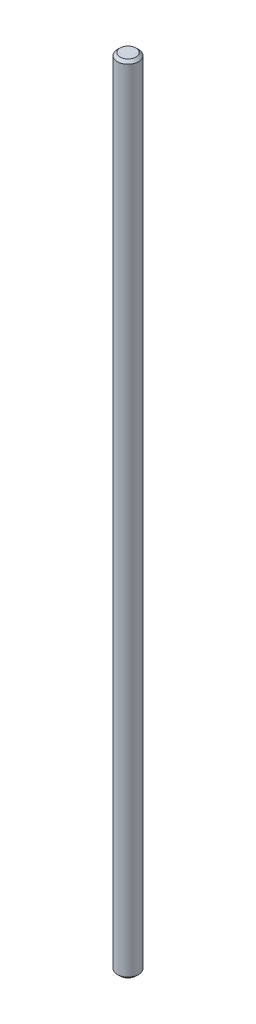
SolidWorks part; units mm, degrees
ref_plane "Front Plane" through (0, 0, 0) normal (0, 0, 1) x (1, 0, 0)
ref_plane "Top Plane" through (0, 0, 0) normal (0, 1, 0) x (1, 0, 0)
ref_plane "Right Plane" through (0, 0, 0) normal (1, 0, 0) x (0, 0, -1)
sketch "Sketch1" plane through (0, 0, 0) normal (0, 1, 0) x (1, 0, 0)
  circle A0 centre (0, 0) radius 4
  dimension "D1" = 8
extrude "Boss-Extrude1" add sketch "Sketch1" along normal blind 300
chamfer "Chamfer1" distance 1 angle 45 2 edges at (0, 300, 4) (0, 0, 4)
